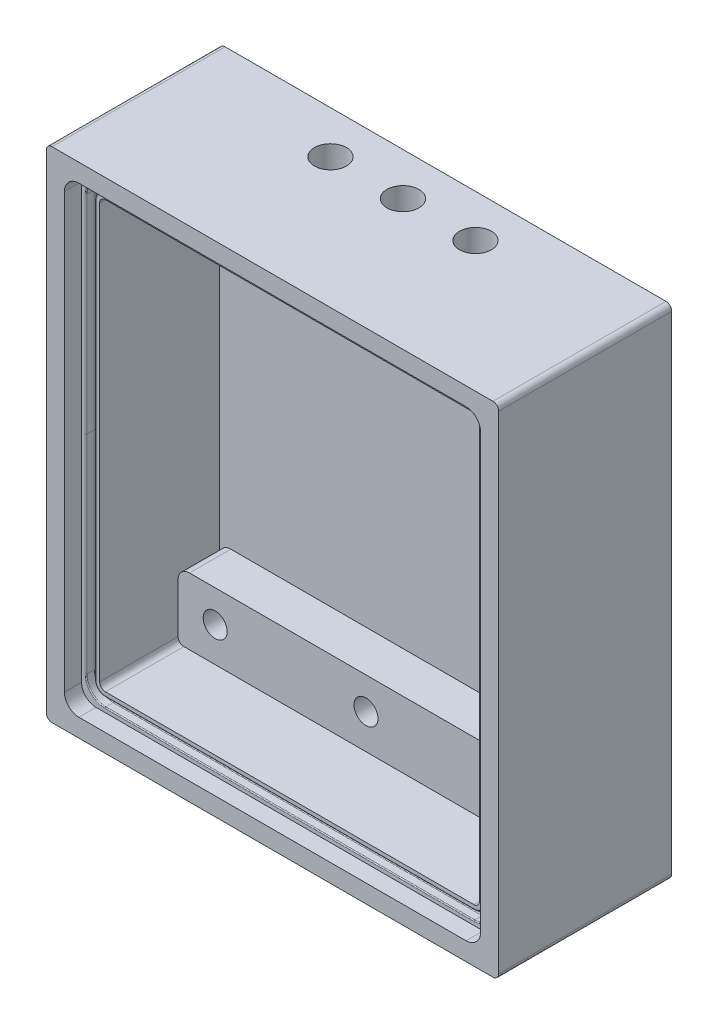
SolidWorks part; units mm, degrees
material "Custom Plastic"
ref_plane "X-Y Datum" through (0, 0, 0) normal (0, 0, 1) x (1, 0, 0)
ref_plane "X-Z Datum" through (0, 0, 0) normal (0, 1, 0) x (1, 0, 0)
ref_plane "Y-Z Datum" through (0, 0, 0) normal (1, 0, 0) x (0, 0, -1)
sketch "Sketch1" plane through (0, 0, 0) normal (0, 0, 1) x (1, 0, 0)
  line L0 (20.066, 103.886) -> (84.074, 103.9495) construction
  line L3 (52.0065, 139.9857) -> (52.1335, 67.8498) construction
  line L7 (12.446, 147.6057) -> (91.694, 147.6057)
  line L8 (12.446, 147.6057) -> (12.446, 60.2298)
  line L9 (12.446, 60.2298) -> (91.694, 60.2298)
  line L10 (91.694, 147.6057) -> (91.694, 60.2298)
  point P2 (52.07, 103.9177)
  dimension "D1" = 67.8498
  dimension "D2" = 103.886
  dimension "D3" = 20.066
  dimension "D4" = 7.62
  dimension "D5" = 72.136
  dimension "D6" = 64.008
  dimension "D7" = 7.62
  dimension "D8" = 7.62
  dimension "D9" = 52.1335
  dimension "D10" = 7.62
extrude "Boss-Extrude2" add sketch "Sketch1" along normal blind 20.32 and the other way blind 10 separate body
shell "Shell2" thickness 6.35
sketch "Sketch2" plane through (0, 0, -3.65) normal (0, 0, 1) x (1, 0, 0)
  line L0 (85.344, 66.5798) -> (85.344, 141.2557) construction
  line L1 (18.796, 141.2557) -> (85.344, 141.2557)
  line L2 (18.796, 141.2557) -> (18.796, 129.5957)
  line L3 (18.796, 129.5957) -> (85.344, 129.5957)
  line L4 (85.344, 141.2557) -> (85.344, 129.5957)
  dimension "D1" = 11.66
extrude "Boss-Extrude3" add sketch "Sketch2" along normal blind 7.23 separate body
ref_plane "Plane1" through (0, 103.9177, 0) normal (0, -1, 0) x (-1, 0, 0)
mirror "Mirror4" about plane through (0, 103.9177, 0) normal (0, -1, 0) of bodies 116
fillet "Fillet1" radius 1 8 edges at (85.344, 141.2557, 8.335) (18.796, 141.2557, 8.335) (18.796, 66.5798, 8.335) (85.344, 66.5798, 8.335) (91.694, 60.2298, 5.16) (12.446, 60.2298, 5.16) (12.446, 147.6057, 5.16) (91.694, 147.6057, 5.16)
fillet "Fillet2" radius 2 2 edges at (18.796, 78.2398, -0.035) (85.344, 78.2398, -0.035)
fillet "Fillet3" radius 2 2 edges at (85.344, 129.5957, -0.035) (18.796, 129.5957, -0.035)
sketch "Sketch3" plane through (0, 0, 3.58) normal (0, 0, 1) x (1, 0, 0)
  circle A1 centre (25.292, 72.644) radius 2.1
  circle A2 centre (51.708, 72.644) radius 2.1
  circle A3 centre (79.14, 72.644) radius 2.1
  dimension "D1" = 4.2
  dimension "D2" = 4.2
  dimension "D3" = 4.2
extrude "Cut-Extrude2" cut sketch "Sketch3" against normal blind 5
mirror "Mirror12" about plane through (0, 103.9177, 0) normal (0, -1, 0) of "Cut-Extrude2"
sketch "Sketch4" plane through (0, 0, 20.32) normal (0, 0, 1) x (1, 0, 0)
  line L0 (12.446, 147.6057) -> (91.694, 147.6057) construction
  line L1 (18.161, 144.4307) -> (85.979, 144.4307)
  line L2 (15.621, 141.8907) -> (15.621, 65.9448)
  line L3 (18.161, 63.4048) -> (85.979, 63.4048)
  line L4 (88.519, 141.8907) -> (88.519, 65.9448)
  line L5 (12.446, 147.6057) -> (12.446, 60.2298) construction
  line L6 (91.694, 147.6057) -> (91.694, 60.2298) construction
  line L7 (12.446, 60.2298) -> (91.694, 60.2298) construction
  arc A4 (15.621, 141.8907) -> (18.161, 144.4307) centre (18.161, 141.8907) cw
  arc A5 (85.979, 63.4048) -> (88.519, 65.9448) centre (85.979, 65.9448) ccw
  arc A6 (15.621, 65.9448) -> (18.161, 63.4048) centre (18.161, 65.9448) ccw
  arc A7 (88.519, 141.8907) -> (85.979, 144.4307) centre (85.979, 141.8907) ccw
  dimension "D5" = 2.54
  dimension "D6" = 2.54
  dimension "D1" = 3.175
  dimension "D2" = 3.175
  dimension "D3" = 3.175
  dimension "D4" = 3.175
extrude "Cut-Extrude3" cut sketch "Sketch4" against normal blind 3
ref_plane "Mid XZ plane" through (0, 103.9177, 0) normal (0, 1, 0) x (1, 0, 0)
sketch "Sketch6" plane through (0, 0, 17.32) normal (0, 0, 1) x (1, 0, 0)
  line L0 (15.621, 141.8907) -> (15.621, 65.9448) construction
  line L1 (19.7485, 142.8432) -> (84.3915, 142.8432)
  line L2 (17.2085, 140.3032) -> (17.2085, 67.5323)
  line L3 (19.7485, 64.9923) -> (84.3915, 64.9923)
  line L4 (86.9315, 140.3032) -> (86.9315, 67.5323)
  line L5 (88.519, 65.9448) -> (88.519, 141.8907) construction
  line L6 (85.979, 144.4307) -> (18.161, 144.4307) construction
  line L7 (18.161, 63.4048) -> (85.979, 63.4048) construction
  arc A0 (19.7485, 64.9923) -> (17.2085, 67.5323) centre (19.7485, 67.5323) cw
  arc A1 (84.3915, 64.9923) -> (86.9315, 67.5323) centre (84.3915, 67.5323) ccw
  arc A2 (86.9315, 140.3032) -> (84.3915, 142.8432) centre (84.3915, 140.3032) ccw
  arc A3 (17.2085, 140.3032) -> (19.7485, 142.8432) centre (19.7485, 140.3032) cw
  dimension "D5" = 2.54
  dimension "D1" = 1.5875
  dimension "D2" = 1.5875
  dimension "D3" = 1.5875
  dimension "D4" = 1.5875
sketch "Sketch5" plane through (0, 103.9177, 0) normal (0, 1, 0) x (1, 0, 0)
  line L1 (16.4147, -15.7325) -> (18.0022, -15.7325)
  line L2 (16.4147, -15.7325) -> (16.4147, -18.9075)
  line L3 (16.4147, -18.9075) -> (18.0022, -18.9075)
  line L4 (18.0022, -15.7325) -> (18.0022, -18.9075)
  line L5 (16.4147, -18.9075) -> (18.0022, -15.7325) construction
  line L6 (18.0022, -18.9075) -> (16.4147, -15.7325) construction
  point P4 (17.2085, -17.32)
  dimension "D1" = 1.5875
  dimension "D2" = 3.175
sweep "Cut-Sweep1" cut profiles "Sketch5" path "Sketch6"
sketch "Sketch7" plane through (0, 147.6057, 0) normal (0, 1, 0) x (1, 0, 0)
  line L0 (52.07, -20.32) -> (52.07, 10) construction
  line L1 (90.694, -20.32) -> (13.446, -20.32) construction
  line L2 (90.694, 10) -> (13.446, 10) construction
  circle A0 centre (52.07, 2.54) radius 2.8067
  circle A1 centre (64.77, 2.54) radius 2.8067
  circle A2 centre (39.37, 2.54) radius 2.8067
  dimension "D1" = 5.6134
  dimension "D4" = 12.7
  dimension "D5" = 12.7
  dimension "D6" = 22.86
extrude "Cut-Extrude4" cut sketch "Sketch7" against normal blind 4.699
mirror "Mirror13" about plane through (0, 103.9177, 0) normal (0, 1, 0) of "Cut-Extrude4"
fillet "Fillet4" radius 0.1588 18 edges at (18.5137, 66.2975, 17.32) (52.07, 65.786, 17.32) (85.6263, 66.2975, 17.32) (86.1377, 103.9177, 17.32) (85.6263, 141.538, 17.32) (52.07, 142.0495, 17.32) (18.5137, 141.538, 17.32) (18.0022, 122.1105, 17.32) (16.4147, 122.1105, 17.32) (17.3912, 142.6606, 17.32) (52.07, 143.637, 17.32) (86.7488, 142.6606, 17.32) (87.7252, 103.9177, 17.32) (86.7488, 65.1749, 17.32) (52.07, 64.1985, 17.32) (17.3912, 65.1749, 17.32) (18.0022, 85.725, 17.32) (16.4147, 85.725, 17.32)
fillet "Fillet5" radius 0.1588 18 edges at (18.5137, 141.538, 15.7325) (52.07, 142.0495, 15.7325) (85.6263, 141.538, 15.7325) (86.1377, 103.9177, 15.7325) (85.6263, 66.2975, 15.7325) (52.07, 65.786, 15.7325) (18.5137, 66.2975, 15.7325) (18.0022, 85.725, 15.7325) (16.4147, 122.1105, 15.7325) (17.3912, 142.6606, 15.7325) (52.07, 143.637, 15.7325) (86.7488, 142.6606, 15.7325) (87.7252, 103.9177, 15.7325) (86.7488, 65.1749, 15.7325) (52.07, 64.1985, 15.7325) (17.3912, 65.1749, 15.7325) (18.0022, 122.1105, 15.7325) (16.4147, 85.725, 15.7325)
